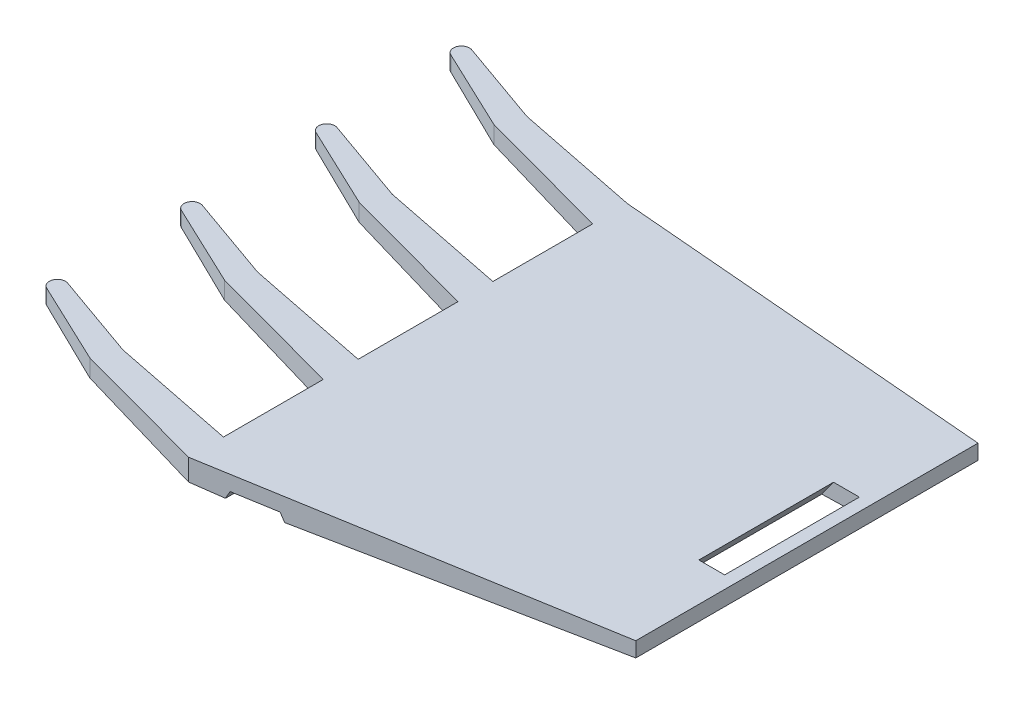
SolidWorks part; units mm, degrees
ref_plane "Front Plane" through (0, 0, 0) normal (0, 0, 1) x (1, 0, 0)
ref_plane "Top Plane" through (0, 0, 0) normal (0, 1, 0) x (1, 0, 0)
ref_plane "Right Plane" through (0, 0, 0) normal (1, 0, 0) x (0, 0, -1)
sketch "Sketch1" plane through (0, 0, 0) normal (0, 1, 0) x (1, 0, 0)
  line L0 (0, 0) -> (0, 71.5794) construction
  line L1 (-58.6522, 71.5794) -> (63.1198, 71.5794) construction
  line L2 (-58.6522, 71.5794) -> (-58.6522, -28) construction
  line L3 (-58.6522, -28) -> (63.1198, -28) construction
  line L4 (63.1198, 71.5794) -> (63.1198, -28) construction
  line L5 (0, 0) -> (63.1198, 0) construction
  line L6 (-58.6522, 71.5794) -> (-58.6522, -28) construction
  line L7 (-58.6522, -28) -> (-13.5566, -28) construction
  line L8 (-13.5566, 71.5794) -> (-58.6522, 71.5794) construction
  line L9 (-13.5566, -28) -> (-13.5566, 71.5794) construction
  line L10 (-40.7118, -20.6376) -> (-13.5566, -28) construction
  line L11 (-58.6522, -12.1395) -> (-40.7118, -20.6376) construction
  line L12 (-57.2198, -9.4206) -> (-58.6522, -12.1395) construction
  line L13 (-38.7799, -15.9391) -> (-57.2198, -9.4206) construction
  line L14 (-13.5566, -21) -> (-38.7799, -15.9391) construction
  line L15 (-13.5566, -1) -> (-13.5566, -21) construction
  line L16 (-13.5566, -1) -> (-40.7118, 6.3624) construction
  line L17 (-40.7118, 6.3624) -> (-58.6522, 14.8605) construction
  line L18 (-58.6522, 14.8605) -> (-57.2198, 17.5794) construction
  line L19 (-57.2198, 17.5794) -> (-38.7799, 11.0609) construction
  line L20 (-38.7799, 11.0609) -> (-13.5566, 6) construction
  line L21 (-13.5566, 26) -> (-13.5566, 6) construction
  line L22 (-13.5566, 26) -> (-40.7118, 33.3624) construction
  line L23 (-40.7118, 33.3624) -> (-58.6522, 41.8605) construction
  line L24 (-58.6522, 41.8605) -> (-57.2198, 44.5794) construction
  line L25 (-57.2198, 44.5794) -> (-38.7799, 38.0609) construction
  line L26 (-38.7799, 38.0609) -> (-13.5566, 33) construction
  line L27 (-13.5566, 53) -> (-13.5566, 33) construction
  line L28 (-13.5566, 53) -> (-40.7118, 60.3624) construction
  line L29 (-40.7118, 60.3624) -> (-58.6522, 68.8605) construction
  line L30 (-58.6522, 68.8605) -> (-57.2198, 71.5794) construction
  line L31 (-57.2198, 71.5794) -> (-38.7799, 65.0609) construction
  line L32 (-38.7799, 65.0609) -> (-13.5566, 60) construction
  line L33 (-40.7118, -20.6376) -> (-13.5566, -28)
  line L34 (-58.6522, -12.1395) -> (-40.7118, -20.6376) construction
  line L35 (-57.2198, -9.4206) -> (-58.6522, -12.1395) construction
  line L36 (-38.7799, -15.9391) -> (-57.2198, -9.4206) construction
  line L37 (-13.5566, -21) -> (-38.7799, -15.9391)
  line L38 (-13.5566, -1) -> (-13.5566, -21)
  line L39 (-13.5566, -1) -> (-40.7118, 6.3624)
  line L40 (-40.7118, 6.3624) -> (-58.6522, 14.8605) construction
  line L41 (-58.6522, 14.8605) -> (-57.2198, 17.5794) construction
  line L42 (-57.2198, 17.5794) -> (-38.7799, 11.0609) construction
  line L43 (-38.7799, 11.0609) -> (-13.5566, 6)
  line L44 (-13.5566, 26) -> (-13.5566, 6)
  line L45 (-13.5566, 26) -> (-40.7118, 33.3624)
  line L46 (-40.7118, 33.3624) -> (-58.6522, 41.8605) construction
  line L47 (-58.6522, 41.8605) -> (-57.2198, 44.5794) construction
  line L48 (-57.2198, 44.5794) -> (-38.7799, 38.0609) construction
  line L49 (-38.7799, 38.0609) -> (-13.5566, 33)
  line L50 (-13.5566, 53) -> (-13.5566, 33)
  line L51 (-13.5566, 53) -> (-40.7118, 60.3624)
  line L52 (-40.7118, 60.3624) -> (-58.6522, 68.8605) construction
  line L53 (-58.6522, 68.8605) -> (-57.2198, 71.5794) construction
  line L54 (-57.2198, 71.5794) -> (-38.7799, 65.0609) construction
  line L55 (-38.7799, 65.0609) -> (-13.5566, 60)
  line L56 (-38.7799, 65.0609) -> (-55.907, 71.1153)
  line L57 (-40.7118, 60.3624) -> (-57.1333, 68.141)
  line L58 (-55.907, 44.1153) -> (-38.7799, 38.0609)
  line L59 (-40.7118, 33.3624) -> (-57.1333, 41.141)
  line L60 (-55.907, 17.1153) -> (-38.7799, 11.0609)
  line L61 (-40.7118, 6.3624) -> (-57.1333, 14.141)
  line L62 (-55.907, -9.8847) -> (-38.7799, -15.9391)
  line L63 (-40.7118, -20.6376) -> (-57.1333, -12.859)
  line L64 (59.995, 71.5794) -> (59.995, -28) construction
  line L65 (59.995, 53.5656) -> (63.1198, 53.5656) construction
  line L67 (59.995, -15.0319) -> (63.1198, -15.0319) construction
  line L72 (63.1198, 53.5656) -> (63.1198, -15.0319)
  line L73 (63.1198, -15.0319) -> (-13.5566, -28)
  line L74 (63.1198, 53.5656) -> (-13.5566, 60)
  arc A0 (-55.907, 71.1153) -> (-57.1333, 68.141) centre (-56.4438, 69.5967) ccw
  arc A1 (-55.907, 44.1153) -> (-57.1333, 41.141) centre (-56.4438, 42.5967) ccw
  arc A2 (-55.907, 17.1153) -> (-57.1333, 14.141) centre (-56.4438, 15.5967) ccw
  arc A3 (-55.907, -9.8847) -> (-57.1333, -12.859) centre (-56.4438, -11.4033) ccw
sketch "Sketch2" plane through (0, 0, 0) normal (0, 0, 1) x (1, 0, 0)
  line L0 (-57.2198, -3) -> (-7.2198, -4.5) construction
  line L1 (-7.2198, -4.5) -> (-6.4314, -3) construction
  line L2 (2.1417, -3) -> (-6.4314, -3) construction
  line L3 (2.1417, -3) -> (2.9301, -4.5) construction
  line L4 (2.9301, -4.5) -> (63.1198, -3) construction
  line L5 (63.1198, 0) -> (63.1198, -3) construction
  line L6 (63.1198, 0) -> (-57.2198, 0) construction
  line L8 (-58.6522, -2.957) -> (-7.2198, -4.5)
  line L9 (-7.2198, -4.5) -> (-6.4314, -3)
  line L10 (2.1417, -3) -> (-6.4314, -3)
  line L11 (2.1417, -3) -> (2.9301, -4.5)
  line L12 (2.9301, -4.5) -> (63.1198, -3)
  line L13 (63.1198, 0) -> (63.1198, -3)
  line L14 (63.1198, 0) -> (-58.6522, 0)
  line L15 (-58.6522, 0) -> (-58.6522, -2.957)
extrude "Boss-Extrude1" add sketch "Sketch2" against normal up to vertex (71.5794 mm away) from vertex at 28 starting at point (-58.6522, 0, 28)
extrude "Cut-Extrude1" cut sketch "Sketch1" against normal through all flip side to cut
sketch "Sketch3" plane through (0, 0, 0) normal (0, 0, 1) x (1, 0, 0)
  line L0 (60.6021, 0) -> (55.4272, 0)
  line L1 (55.4272, 0) -> (53.078, -3.2503)
  line L2 (53.078, -3.2503) -> (58.456, -3.1162)
  line L3 (58.456, -3.1162) -> (60.6021, 0)
  line L4 (63.1198, 0) -> (-57.2198, 0) construction
  line L5 (2.9301, -4.5) -> (63.1198, -3) construction
  line L8 (59.995, 0) -> (57.8382, -3.1316) construction
  line L9 (53.696, -3.2349) -> (56.0341, 0) construction
  line L10 (23.9187, -44.4327) -> (62.7128, 9.2402) construction
  line L11 (65.1664, 7.5088) -> (-6.4848, -96.5277) construction
  line L12 (59.529, -1.5581) -> (58.9166, -1.5658) construction
  line L13 (54.865, -1.6174) -> (54.2526, -1.6251) construction
  dimension "D1" = 0.5
extrude "Cut-Extrude2" cut sketch "Sketch3" against normal up to vertex from vertex
